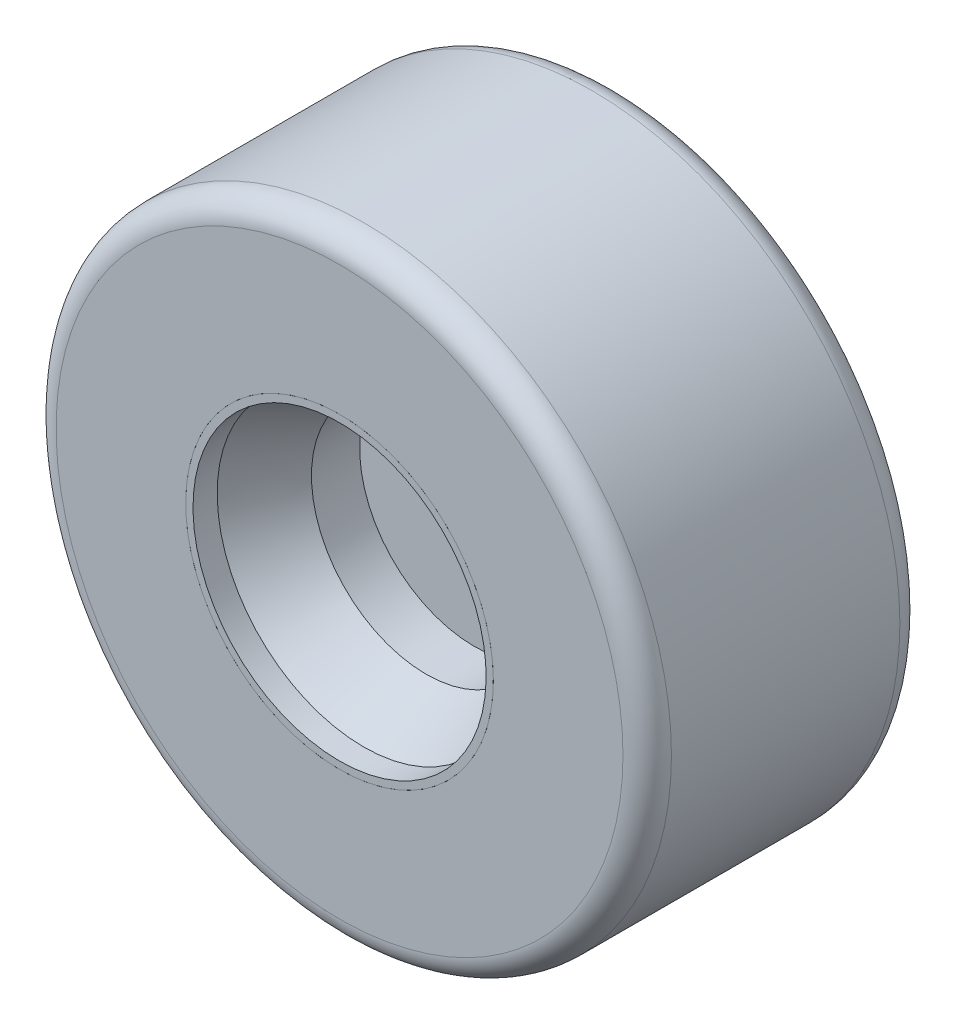
SolidWorks part; units mm, degrees
ref_plane "Front Plane" through (0, 0, 0) normal (0, 0, 1) x (1, 0, 0)
ref_plane "Top Plane" through (0, 0, 0) normal (0, 1, 0) x (1, 0, 0)
ref_plane "Right Plane" through (0, 0, 0) normal (1, 0, 0) x (0, 0, -1)
sketch "Sketch2" plane through (0, 0, 0) normal (1, 0, 0) x (0, 0, -1)
  line L0 (0, 35.7524) -> (0, -35.7524) construction
  line L1 (21.38, 4.6171) -> (-21.38, 4.6171)
  line L2 (-21.38, 4.6171) -> (-47.15, 17.7476)
  line L3 (-47.15, 17.7476) -> (-57.15, 17.7476)
  line L4 (-57.15, 17.7476) -> (-57.15, 14.7476)
  line L5 (-57.15, 14.7476) -> (-47.15, 14.7476)
  line L6 (-47.15, 14.7476) -> (-21.38, 1.6171)
  line L7 (-21.38, 1.6171) -> (-1.5, 1.6171)
  line L8 (-1.5, 1.6171) -> (-1.5, -35.7524)
  line L9 (-1.5, -35.7524) -> (1.5, -35.7524)
  line L10 (0, -35.7524) -> (0, -45.7524) construction
  line L11 (-57.4407, -45.7524) -> (57.4407, -45.7524) construction
  line L12 (1.5, 1.6171) -> (1.5, -35.7524)
  line L13 (57.15, 14.7476) -> (47.15, 14.7476)
  line L14 (57.15, 17.7476) -> (57.15, 14.7476)
  line L15 (47.15, 17.7476) -> (57.15, 17.7476)
  line L16 (47.15, 14.7476) -> (21.38, 1.6171)
  line L17 (21.38, 4.6171) -> (47.15, 17.7476)
  line L18 (21.38, 1.6171) -> (1.5, 1.6171)
  point P4 (0, 0)
  point P16 (0, -45.7524)
  point P27 (0, 4.6171)
  dimension "D1" = 21.38
  dimension "D2" = 57.15
  dimension "D3" = 10
  dimension "D4" = 10
  dimension "D5" = 3
  dimension "D6" = 153
  dimension "D7" = 1.5
  dimension "D8" = 63.5
  dimension "D9" = 10
revolve "Revolve1" add sketch "Sketch2" angle 360 about L11
sketch "Sketch3" plane through (0, 0, 1.5) normal (0, 0, 1) x (1, 0, 0)
  circle A0 centre (0, -45.7524) radius 20
  circle A1 centre (20, -45.7524) radius 4
  circle A2 centre (0, -25.7524) radius 4
  circle A3 centre (-20, -45.7524) radius 4
  circle A4 centre (0, -65.7524) radius 4
  dimension "D1" = 40
  dimension "D2" = 8
  dimension "D3" = 8
  dimension "D4" = 8
  dimension "D5" = 8
extrude "Cut-Extrude1" cut sketch "Sketch3" against normal blind 10 contours A0 A2 | A0 A2 | A0 A3 | A0 A3 | A0 A1 | A0 A1 | A0 A4
sketch "Sketch4" plane through (0, 0, 0) normal (1, 0, 0) x (0, 0, -1)
  line L0 (0, 4.6171) -> (0, -96.122) construction
  line L1 (21.38, 4.6171) -> (-21.38, 4.6171) construction
  line L2 (-21.38, -96.122) -> (21.38, -96.122) construction
  line L3 (-47.15, 81.2476) -> (47.15, 81.2476)
  line L4 (57.15, 17.7476) -> (57.15, 71.2476)
  line L5 (-57.15, 17.7476) -> (-57.15, 71.2476)
  line L6 (-57.15, 17.7476) -> (-47.15, 17.7476)
  line L7 (-47.15, 17.7476) -> (-21.38, 4.6171)
  line L8 (-21.38, 4.6171) -> (21.38, 4.6171)
  line L9 (21.38, 4.6171) -> (47.15, 17.7476)
  line L10 (47.15, 17.7476) -> (57.15, 17.7476)
  line L11 (-47.15, 75.1029) -> (47.15, 75.1029)
  line L12 (49.65, 72.6029) -> (49.65, 26.6029)
  line L13 (49.65, 26.6029) -> (45.35, 26.6029)
  line L14 (45.35, 26.6029) -> (19.4638, 13.7083)
  line L15 (19.4638, 13.7083) -> (-19.4638, 13.7083)
  line L16 (-19.4638, 13.7083) -> (-45.35, 26.6029)
  line L17 (-45.35, 26.6029) -> (-49.65, 26.6029)
  line L18 (-49.65, 26.6029) -> (-49.65, 72.6029)
  line L19 (-166.0918, -45.7524) -> (166.0918, -45.7524) construction
  arc A0 (57.15, 71.2476) -> (47.15, 81.2476) centre (47.15, 71.2476) ccw
  arc A1 (-57.15, 71.2476) -> (-47.15, 81.2476) centre (-47.15, 71.2476) cw
  arc A2 (47.15, 75.1029) -> (49.65, 72.6029) centre (47.15, 72.6029) cw
  arc A3 (-47.15, 75.1029) -> (-49.65, 72.6029) centre (-47.15, 72.6029) ccw
  point P6 (0, -45.7524)
  point P33 (-49.65, 49.6029)
  point P41 (0, -45.7524)
  dimension "D2" = 10
  dimension "D5" = 2.5
  dimension "D1" = 127
  dimension "D3" = 7.5
  dimension "D4" = 7.5
  dimension "D6" = 46
  dimension "D7" = 4.3
  dimension "D8" = 28.92
  dimension "D9" = 46
  dimension "D10" = 4.3
  dimension "D11" = 28.92
revolve "Revolve2" add sketch "Sketch4" angle 360 about L19
